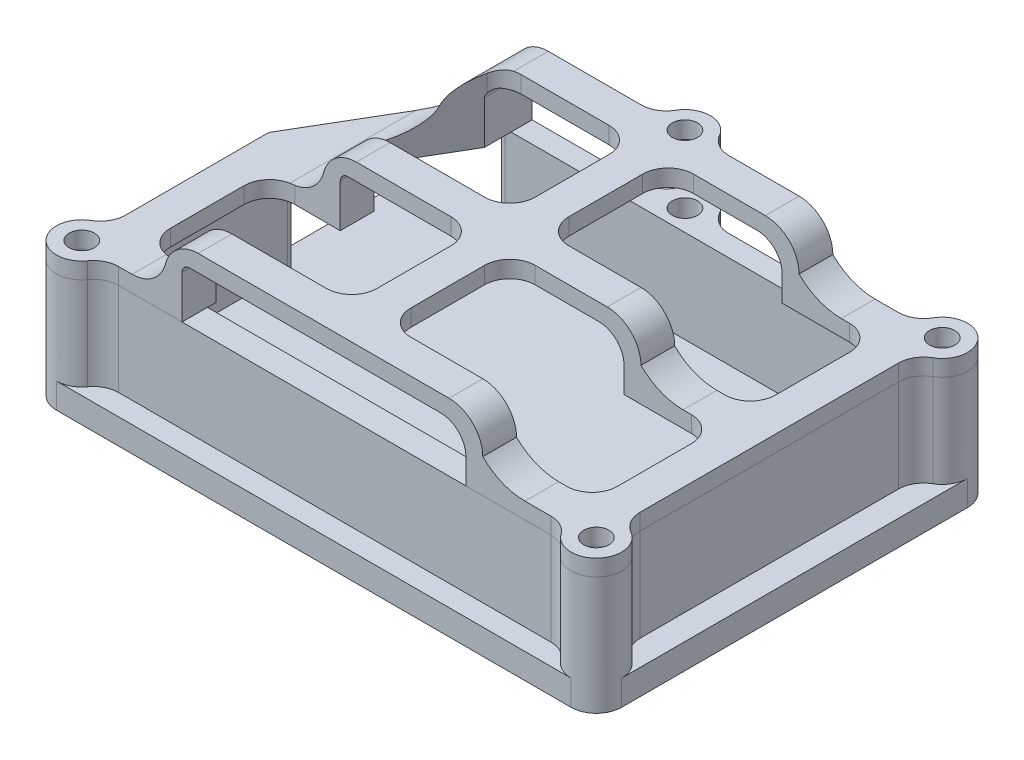
SolidWorks part; units mm, degrees
other "Markup1"
sketch "Sketch9" plane through (-33.5, 0, 23.5) normal (-0.9335, -0.3143, 0.1726) x (0.0607, 0.3358, 0.94)
material "ABS"
ref_plane "Front Plane" through (0, 0, 0) normal (0, 0, 1) x (1, 0, 0)
ref_plane "Top Plane" through (0, 0, 0) normal (0, 1, 0) x (1, 0, 0)
ref_plane "Right Plane" through (0, 0, 0) normal (1, 0, 0) x (0, 0, -1)
sketch "Sketch5" plane through (0, 0, 0) normal (0, 1, 0) x (1, 0, 0)
  line L1 (-28, -18) -> (28, -18) construction
  line L2 (-28, -18) -> (-28, 18) construction
  line L3 (-28, 18) -> (28, 18) construction
  line L4 (28, -18) -> (28, 18) construction
  line L5 (-28, -18) -> (28, 18) construction
  line L6 (-28, 18) -> (28, -18) construction
  line L8 (30.5, -20.5) -> (30.5, 20.5) construction
  line L10 (-5.1962, 20.5) -> (-27.5, 20.5)
  line L14 (-30.5, 17.5) -> (-30.5, -15.3038)
  line L16 (0, 0) -> (0, 20.5) construction
  line L20 (-30.5, 7.9079) -> (-28, 7.9079)
  line L25 (-30.5, -23.5) -> (30.5, -23.5)
  line L26 (33.5, -20.5) -> (33.5, 20.5)
  line L27 (30.5, 23.5) -> (0, 23.5)
  line L28 (-30.5, 20.5) -> (30.5, 20.5) construction
  line L29 (-30.5, -20.5) -> (-30.5, 20.5) construction
  line L30 (-30.5, -20.5) -> (30.5, -20.5) construction
  arc A1 (33.5, 20.5) -> (30.5, 23.5) centre (30.5, 20.5) ccw
  arc A2 (30.5, -23.5) -> (33.5, -20.5) centre (30.5, -20.5) ccw
  arc A3 (-32, -17.9019) -> (-30.5, -23.5) centre (-30.5, -20.5) ccw
  circle A4 centre (0, 20.5) radius 1.5
  circle A5 centre (30.5, 20.5) radius 1.5
  circle A6 centre (30.5, -20.5) radius 1.5
  circle A7 centre (-30.5, -20.5) radius 1.5
  arc A8 (0, 23.5) -> (-2.5981, 22) centre (0, 20.5) ccw
  arc A9 (-27.5, 20.5) -> (-30.5, 17.5) centre (-27.5, 17.5) ccw
  arc A10 (-30.5, -15.3038) -> (-32, -17.9019) centre (-33.5, -15.3038) cw
  arc A11 (-2.5981, 22) -> (-5.1962, 20.5) centre (-5.1962, 23.5) cw
  point P0 (0, 0)
  point P10 (0, 0)
  dimension "D7" = 6
  dimension "D8" = 6
  dimension "D9" = 6
  dimension "D10" = 3
  dimension "D11" = 3
  dimension "D12" = 3
  dimension "D13" = 3
  dimension "D5" = 3
  dimension "D16" = 3
  dimension "D19" = 2.5
  dimension "D1" = 36
  dimension "D2" = 56
  dimension "D4" = 2.5
  dimension "D14" = 2.5
  dimension "D15" = 2.5
  dimension "D17" = 2.5
  dimension "D18" = 2.5
  dimension "D3" = 2.5
extrude "Boss-Extrude2" add sketch "Sketch5" along normal blind 3
sketch "Sketch6" plane through (0, 3, 0) normal (0, 1, 0) x (1, 0, 0)
  line L0 (-30.5, 1.3894) -> (-30.5, -15.3038)
  line L1 (26, 18) -> (-18.8542, 18)
  line L2 (28, 16) -> (28, -16)
  line L3 (26, -18) -> (-26, -18)
  line L4 (-28, 1.3894) -> (-28, -16)
  line L5 (28, 18) -> (-28, -18) construction
  line L6 (28, -18) -> (0, 0) construction
  line L8 (30.5, 15.3038) -> (30.5, -15.3038)
  line L10 (25.3038, 20.5) -> (5.1962, 20.5)
  line L11 (25.6266, -21) -> (-25.6266, -21)
  line L12 (-5.1962, 20.5) -> (-18.8542, 20.5)
  line L13 (-29.5, 2.3894) -> (-29, 2.3894)
  line L14 (-19.8542, 19) -> (-19.8542, 19.5)
  line L15 (-31.9416, 20.5339) -> (-28, 18) construction
  line L16 (-30.5, -23.5) -> (30.5, -23.5) construction
  arc A0 (-5.1962, 20.5) -> (-2.5981, 22) centre (-5.1962, 23.5) ccw construction
  arc A1 (-32, -17.9019) -> (-30.5, -15.3038) centre (-33.5, -15.3038) ccw construction
  arc A2 (-5.1962, 20.5) -> (-2.5981, 22) centre (-5.1962, 23.5) ccw
  arc A3 (-32, -17.9019) -> (-30.5, -15.3038) centre (-33.5, -15.3038) ccw
  arc A4 (-32, -17.9019) -> (-28.0633, -22.25) centre (-30.5, -20.5) ccw
  arc A6 (32, 17.9019) -> (27.9019, 22) centre (30.5, 20.5) ccw
  arc A7 (28.0633, -22.25) -> (32, -17.9019) centre (30.5, -20.5) ccw
  arc A8 (2.5981, 22) -> (-2.5981, 22) centre (0, 20.5) ccw
  circle A9 centre (0, 20.5) radius 1.5
  circle A10 centre (30.5, 20.5) radius 1.5
  circle A11 centre (30.5, -20.5) radius 1.5
  circle A12 centre (-30.5, -20.5) radius 1.5
  circle A13 centre (-30.5, -20.5) radius 1.5 construction
  arc A15 (-25.6266, -21) -> (-28.0633, -22.25) centre (-25.6266, -24) ccw
  arc A16 (30.5, -15.3038) -> (32, -17.9019) centre (33.5, -15.3038) ccw
  arc A17 (25.6266, -21) -> (28.0633, -22.25) centre (25.6266, -24) cw
  arc A18 (32, 17.9019) -> (30.5, 15.3038) centre (33.5, 15.3038) ccw
  arc A19 (27.9019, 22) -> (25.3038, 20.5) centre (25.3038, 23.5) cw
  arc A20 (2.5981, 22) -> (5.1962, 20.5) centre (5.1962, 23.5) ccw
  arc A21 (-26, -18) -> (-28, -16) centre (-26, -16) cw
  arc A22 (28, -16) -> (26, -18) centre (26, -16) cw
  arc A23 (26, 18) -> (28, 16) centre (26, 16) cw
  arc A25 (-19.8542, 19.5) -> (-18.8542, 20.5) centre (-18.8542, 19.5) cw
  arc A26 (-19.8542, 19) -> (-18.8542, 18) centre (-18.8542, 19) ccw
  arc A27 (-29, 2.3894) -> (-28, 1.3894) centre (-29, 1.3894) cw
  arc A28 (-29.5, 2.3894) -> (-30.5, 1.3894) centre (-29.5, 1.3894) ccw
  circle A29 centre (0, 20.5) radius 1.5 construction
  point P0 (0, 0)
  dimension "D3" = 3
  dimension "D4" = 2
  dimension "D5" = 1
  dimension "D6" = 3
  dimension "D8" = 3
  dimension "D1" = 36
  dimension "D2" = 56
  dimension "D7" = 2.5
  dimension "D9" = 2.5
  dimension "D10" = 2.5
extrude "Boss-Extrude3" add sketch "Sketch6" along normal blind 11
sketch "Sketch7" plane through (0, 14, 0) normal (0, 1, 0) x (1, 0, 0)
  line L1 (-30.3621, 1.8962) -> (-19.7162, 20.0068)
  line L2 (-26.5, -14) -> (-26.5, -5.25)
  line L3 (-23.151, 6.2703) -> (-18.0075, 15.0203)
  line L4 (-15.4213, 16.5) -> (-5, 16.5)
  line L5 (26.5, 13.5) -> (26.5, 4.75)
  line L6 (23.5, -17) -> (5, -17)
  line L7 (-5, 1.75) -> (-20.5647, 1.75)
  line L8 (-5, -2.25) -> (-23.5, -2.25)
  line L9 (2, -14) -> (2, -5.25)
  line L10 (23.5, 1.75) -> (5, 1.75)
  line L11 (-25.6266, -21) -> (25.6266, -21)
  line L12 (30.5, -15.3038) -> (30.5, 15.3038)
  line L13 (25.3038, 20.5) -> (5.1962, 20.5)
  line L14 (-5.1962, 20.5) -> (-18.8542, 20.5)
  line L15 (-19.8542, 19.5) -> (-19.8542, 19)
  line L16 (-18.8542, 18) -> (26, 18)
  line L17 (28, 16) -> (28, -16)
  line L18 (26, -18) -> (-26, -18)
  line L19 (-28, -16) -> (-28, 1.3894)
  line L20 (-29, 2.3894) -> (-29.5, 2.3894)
  line L21 (-30.5, 1.3894) -> (-30.5, -15.3038)
  line L22 (-25.6266, -21) -> (25.6266, -21)
  line L23 (30.5, -15.3038) -> (30.5, 15.3038)
  line L24 (25.3038, 20.5) -> (5.1962, 20.5)
  line L25 (-5.1962, 20.5) -> (-18.8542, 20.5)
  line L32 (-30.5, 1.3894) -> (-30.5, -15.3038)
  line L33 (-2, -14) -> (-2, -5.25)
  line L34 (23.5, -2.25) -> (5, -2.25)
  line L35 (5, 16.5) -> (23.5, 16.5)
  line L36 (-5, -17) -> (-23.5, -17)
  line L37 (-2, 4.75) -> (-2, 13.5)
  line L41 (2, 4.75) -> (2, 13.5)
  line L43 (26.5, -5.25) -> (26.5, -14)
  arc A0 (-18.8542, 20.5) -> (-19.8542, 19.5) centre (-18.8542, 19.5) ccw construction
  arc A1 (-29.5, 2.3894) -> (-30.5, 1.3894) centre (-29.5, 1.3894) ccw construction
  arc A2 (-18.8542, 20.5) -> (-19.7162, 20.0068) centre (-18.8542, 19.5) ccw
  arc A3 (-30.3621, 1.8962) -> (-30.5, 1.3894) centre (-29.5, 1.3894) ccw
  arc A4 (2, -5.25) -> (5, -2.25) centre (5, -5.25) cw
  arc A5 (2, -14) -> (5, -17) centre (5, -14) ccw
  arc A6 (26.5, -14) -> (23.5, -17) centre (23.5, -14) cw
  arc A7 (23.5, -2.25) -> (26.5, -5.25) centre (23.5, -5.25) cw
  arc A8 (23.5, 1.75) -> (26.5, 4.75) centre (23.5, 4.75) ccw
  arc A9 (23.5, 16.5) -> (26.5, 13.5) centre (23.5, 13.5) cw
  arc A10 (2, 4.75) -> (5, 1.75) centre (5, 4.75) ccw
  arc A11 (5, 16.5) -> (2, 13.5) centre (5, 13.5) ccw
  arc A12 (-18.0075, 15.0203) -> (-15.4213, 16.5) centre (-15.4213, 13.5) cw
  arc A13 (-5, 16.5) -> (-2, 13.5) centre (-5, 13.5) cw
  arc A14 (-2, 4.75) -> (-5, 1.75) centre (-5, 4.75) cw
  arc A15 (-2, -5.25) -> (-5, -2.25) centre (-5, -5.25) ccw
  arc A16 (-2, -14) -> (-5, -17) centre (-5, -14) cw
  arc A17 (-26.5, -14) -> (-23.5, -17) centre (-23.5, -14) ccw
  arc A18 (-23.5, -2.25) -> (-26.5, -5.25) centre (-23.5, -5.25) ccw
  arc A19 (-25.6266, -21) -> (-28.0633, -22.25) centre (-25.6266, -24) ccw
  arc A20 (28.0633, -22.25) -> (25.6266, -21) centre (25.6266, -24) ccw
  arc A21 (28.0633, -22.25) -> (32, -17.9019) centre (30.5, -20.5) ccw
  arc A22 (30.5, -15.3038) -> (32, -17.9019) centre (33.5, -15.3038) ccw
  arc A23 (32, 17.9019) -> (30.5, 15.3038) centre (33.5, 15.3038) ccw
  arc A24 (32, 17.9019) -> (27.9019, 22) centre (30.5, 20.5) ccw
  arc A25 (25.3038, 20.5) -> (27.9019, 22) centre (25.3038, 23.5) ccw
  arc A26 (2.5981, 22) -> (5.1962, 20.5) centre (5.1962, 23.5) ccw
  arc A27 (2.5981, 22) -> (-2.5981, 22) centre (0, 20.5) ccw
  arc A28 (-5.1962, 20.5) -> (-2.5981, 22) centre (-5.1962, 23.5) ccw
  arc A29 (-18.8542, 20.5) -> (-19.8542, 19.5) centre (-18.8542, 19.5) ccw
  arc A30 (-19.8542, 19) -> (-18.8542, 18) centre (-18.8542, 19) ccw
  arc A31 (28, 16) -> (26, 18) centre (26, 16) ccw
  arc A32 (26, -18) -> (28, -16) centre (26, -16) ccw
  arc A33 (-28, -16) -> (-26, -18) centre (-26, -16) ccw
  arc A34 (-28, 1.3894) -> (-29, 2.3894) centre (-29, 1.3894) ccw
  arc A35 (-29.5, 2.3894) -> (-30.5, 1.3894) centre (-29.5, 1.3894) ccw
  arc A36 (-32, -17.9019) -> (-30.5, -15.3038) centre (-33.5, -15.3038) ccw
  arc A37 (-32, -17.9019) -> (-28.0633, -22.25) centre (-30.5, -20.5) ccw
  arc A38 (-25.6266, -21) -> (-28.0633, -22.25) centre (-25.6266, -24) ccw
  arc A39 (28.0633, -22.25) -> (25.6266, -21) centre (25.6266, -24) ccw
  arc A40 (28.0633, -22.25) -> (32, -17.9019) centre (30.5, -20.5) ccw
  arc A41 (30.5, -15.3038) -> (32, -17.9019) centre (33.5, -15.3038) ccw
  arc A42 (32, 17.9019) -> (30.5, 15.3038) centre (33.5, 15.3038) ccw
  arc A43 (32, 17.9019) -> (27.9019, 22) centre (30.5, 20.5) ccw
  arc A44 (25.3038, 20.5) -> (27.9019, 22) centre (25.3038, 23.5) ccw
  arc A45 (2.5981, 22) -> (5.1962, 20.5) centre (5.1962, 23.5) ccw
  arc A46 (2.5981, 22) -> (-2.5981, 22) centre (0, 20.5) ccw
  arc A47 (-5.1962, 20.5) -> (-2.5981, 22) centre (-5.1962, 23.5) ccw
  arc A55 (-32, -17.9019) -> (-30.5, -15.3038) centre (-33.5, -15.3038) ccw
  arc A56 (-32, -17.9019) -> (-28.0633, -22.25) centre (-30.5, -20.5) ccw
  arc A57 (-20.5647, 1.75) -> (-23.151, 6.2703) centre (-20.5647, 4.75) cw
  circle A58 centre (0, 20.5) radius 1.5 construction
  circle A59 centre (30.5, 20.5) radius 1.5 construction
  circle A60 centre (30.5, -20.5) radius 1.5 construction
  circle A61 centre (-30.5, -20.5) radius 1.5 construction
  circle A62 centre (0, 20.5) radius 1.5
  circle A63 centre (30.5, 20.5) radius 1.5
  circle A64 centre (30.5, -20.5) radius 1.5
  circle A65 centre (-30.5, -20.5) radius 1.5
  point P93 (-2, 1.75)
  point P96 (-2, -2.25)
  dimension "D7" = 3
  dimension "D2" = 4
  dimension "D3" = 4
  dimension "D4" = 4
  dimension "D5" = 4
  dimension "D6" = 4
  dimension "D1" = 0
extrude "Boss-Extrude4" add sketch "Sketch7" along normal blind 8 separate body
sketch "Sketch12" plane through (0, 0, 0) normal (0, 0, 1) x (1, 0, 0)
  line L13 (33.5, 14) -> (33.5, 22) construction
  line L14 (-33.5, 14) -> (33.5, 14)
  line L15 (-33.5, 14) -> (-33.5, 15.9355)
  line L16 (-33.5, 15.9355) -> (-24.0379, 15.9355)
  line L17 (33.5, 14) -> (33.5, 15.9355)
  line L18 (-25.6266, 22) -> (25.6266, 22) construction
  line L19 (-15.4213, 22) -> (13.5359, 22)
  line L21 (22.5356, 15.9355) -> (33.5, 15.9355)
  line L23 (-33.5, 15.9355) -> (-33.5, 22)
  line L24 (-33.5, 22) -> (-16.2036, 22)
  line L25 (13.5359, 22) -> (33.5, 22)
  line L26 (33.5, 22) -> (33.5, 15.9355)
  line L27 (-18.1103, 14) -> (-18.1103, 19.0979)
  line L28 (-17.2082, 20) -> (12.5359, 20)
  line L29 (15.5359, 17) -> (15.5359, 14)
  line L30 (15.5359, 14) -> (-18.1103, 14)
  arc A4 (-16.2036, 22) -> (-20.1103, 18.8593) centre (-16.2036, 18) ccw
  arc A5 (17.5359, 18) -> (13.5359, 22) centre (13.5359, 18) ccw
  arc A6 (-20.1103, 18.8593) -> (-24.0379, 15.9355) centre (-24.0379, 20.0354) cw
  arc A7 (17.5359, 18) -> (22.5356, 15.9355) centre (22.5356, 23.0217) ccw
  arc A10 (-17.2082, 20) -> (-18.1103, 19.0979) centre (-17.2082, 19.0979) ccw
  arc A11 (15.5359, 17) -> (12.5359, 20) centre (12.5359, 17) ccw
  dimension "D1" = 2
  dimension "D2" = 2
  dimension "D3" = 2
extrude "Cut-Extrude1" cut sketch "Sketch12" against normal mid plane 50
other "Save Bodies1"
